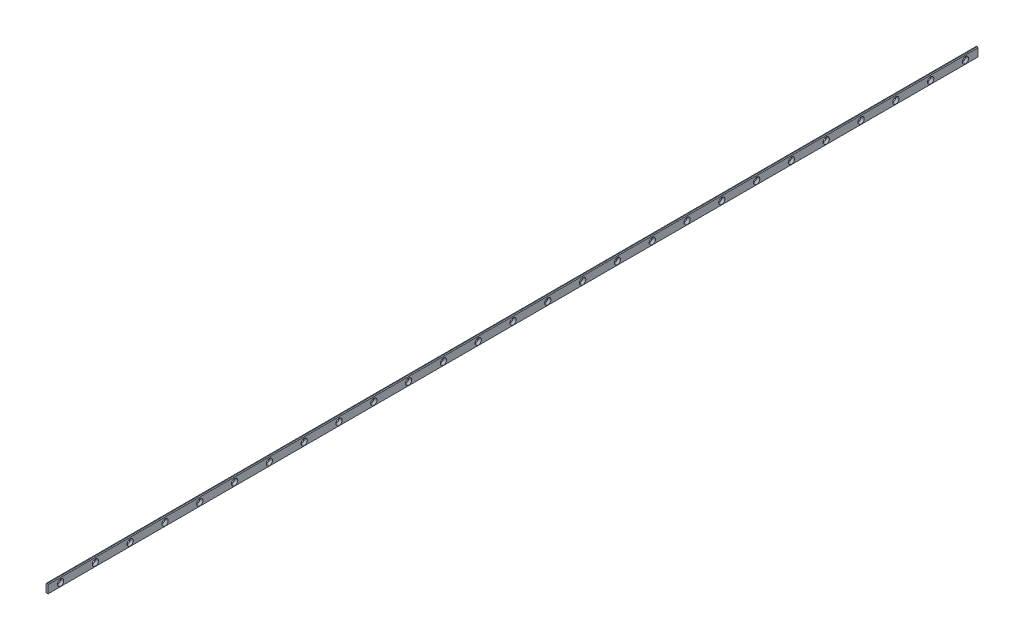
SolidWorks part; units mm, degrees
material "Plain Carbon Steel"
ref_plane "Front Plane" through (0, 0, 0) normal (0, 0, 1) x (1, 0, 0)
ref_plane "Top Plane" through (0, 0, 0) normal (0, 1, 0) x (1, 0, 0)
ref_plane "Right Plane" through (0, 0, 0) normal (1, 0, 0) x (0, 0, -1)
sketch "Sketch1" plane through (0, 0, 0) normal (0, 0, 1) x (1, 0, 0)
  line L1 (-1.5, -6.25) -> (1.5, -6.25)
  line L2 (-1.5, -6.25) -> (-1.5, 6.25)
  line L3 (-1.5, 6.25) -> (1.5, 6.25)
  line L4 (1.5, -6.25) -> (1.5, 6.25)
  line L5 (-1.5, -6.25) -> (1.5, 6.25) construction
  line L6 (-1.5, 6.25) -> (1.5, -6.25) construction
  point P0 (0, 0)
  dimension "D1" = 12.5
  dimension "D2" = 3
extrude "Boss-Extrude1" add sketch "Sketch1" along normal mid plane 1336
sketch "Sketch2" plane through (1.5, 0, 0) normal (1, 0, 0) x (0, 0, -1)
  line L0 (-668, -6.25) -> (668, -6.25) construction
  circle A0 centre (0, -1.25) radius 2
  dimension "D2" = 4
  dimension "D1" = 5
extrude "Cut-Extrude1" cut sketch "Sketch2" against normal blind 10
chamfer "Chamfer1" distance 2.5 angle 45 1 edges at (1.5, -1.25, -2)
pattern_linear "LPattern1" count 14 spacing 50 along (0, 0, 1) count 14 spacing 50 along (0, 0, -1) of "Cut-Extrude1", "Chamfer1"
chamfer "Chamfer2" distance 1 angle 45 2 edges at (-1.5, 6.25, 0) (1.5, 6.25, 0)
